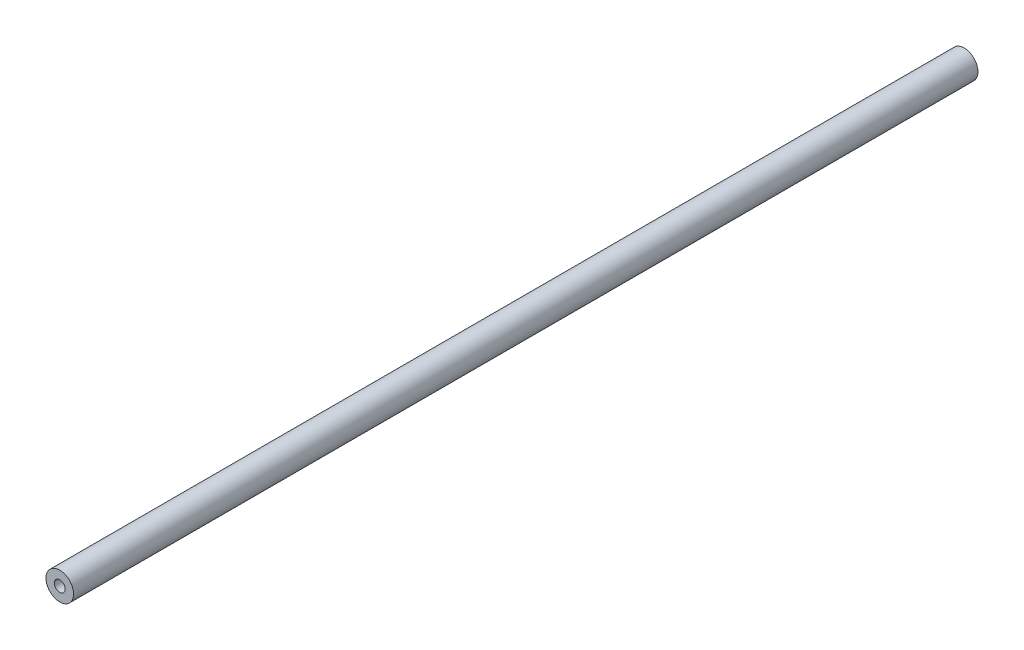
SolidWorks part; units mm, degrees
material "6061 Alloy"
ref_plane "Front Plane" through (0, 0, 0) normal (0, 0, 1) x (1, 0, 0)
ref_plane "Top Plane" through (0, 0, 0) normal (0, 1, 0) x (1, 0, 0)
ref_plane "Right Plane" through (0, 0, 0) normal (1, 0, 0) x (0, 0, -1)
sketch "Sketch1" plane through (0, 0, 0) normal (0, 0, 1) x (1, 0, 0)
  circle A0 centre (0, 0) radius 6.35
  dimension "D1" = 12.7
extrude "Boss-Extrude2" add sketch "Sketch1" along normal blind 416.433
hole_wizard "M6x1.0 Tapped Hole1" positions "Sketch3" profile "Sketch2" tap size "M6x1.0" standard "ANSI Metric" end condition up to next
sketch "Sketch3" plane through (0, 0, 416.433) normal (0, 0, 1) x (1, 0, 0)
  point P0 (0, 0)
sketch "Sketch2" plane through (0, 0, 416.433) normal (1, 0, 0) x (0, -1, 0)
  line L0 (0, 0) -> (0, 416.433)
  line L1 (0, 416.433) -> (2.5, 416.433)
  line L2 (2.5, 416.433) -> (2.5, 0)
  line L5 (2.5, 0) -> (0, 0)
  line L11 (0, -6.35) -> (0, 107.95) construction
  dimension "Thread Major Dia." = 5
  dimension "Thru Tap Drill Depth" = 416.433
